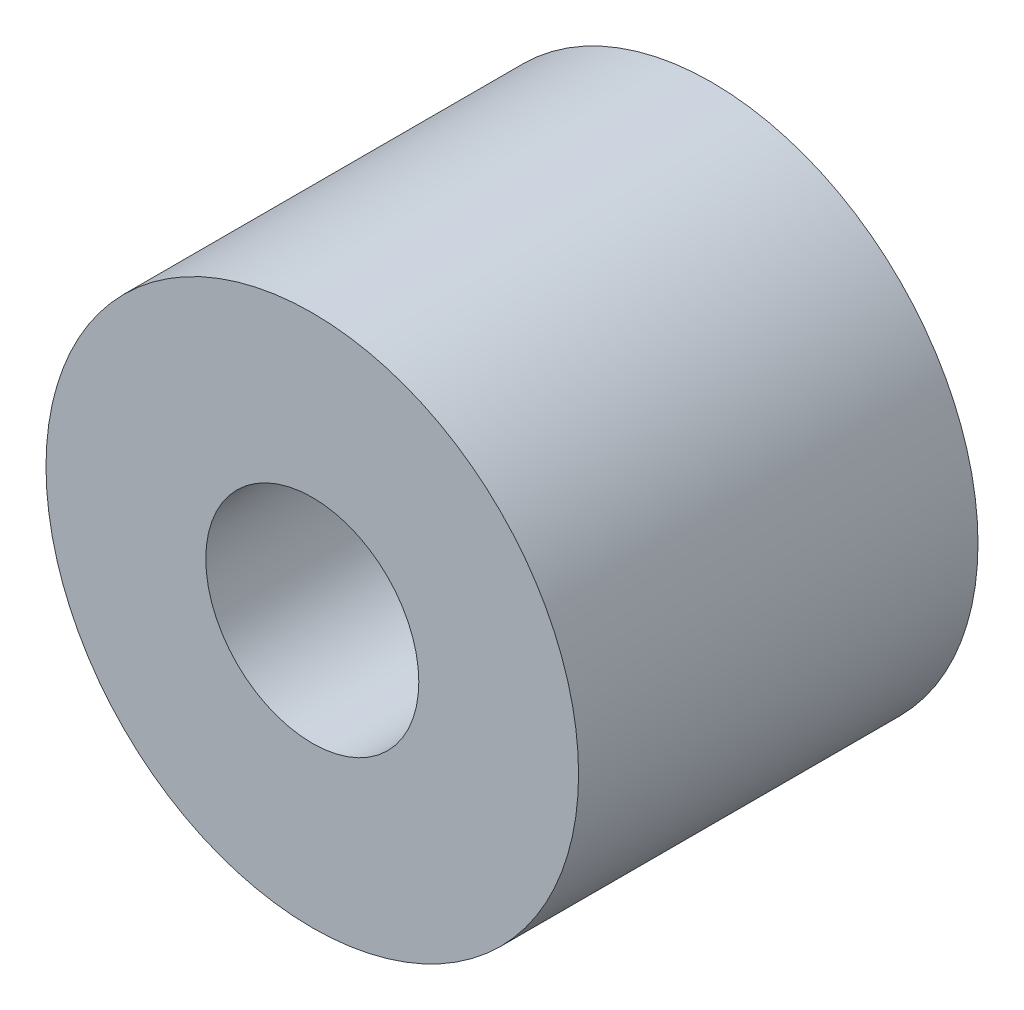
SolidWorks part; units mm, degrees
ref_plane "Plano frontal" through (0, 0, 0) normal (0, 0, 1) x (1, 0, 0)
ref_plane "Plano superior" through (0, 0, 0) normal (0, 1, 0) x (1, 0, 0)
ref_plane "Plano direito" through (0, 0, 0) normal (1, 0, 0) x (0, 0, -1)
sketch "Esboço1" plane through (0, 0, 0) normal (0, 0, 1) x (1, 0, 0)
  circle A0 centre (0, 0) radius 1.6
  circle A1 centre (0, 0) radius 4
  dimension "D1" = 3.2
  dimension "D2" = 8
extrude "Ressalto-extrusão1" add sketch "Esboço1" along normal mid plane 6 from offset 0
